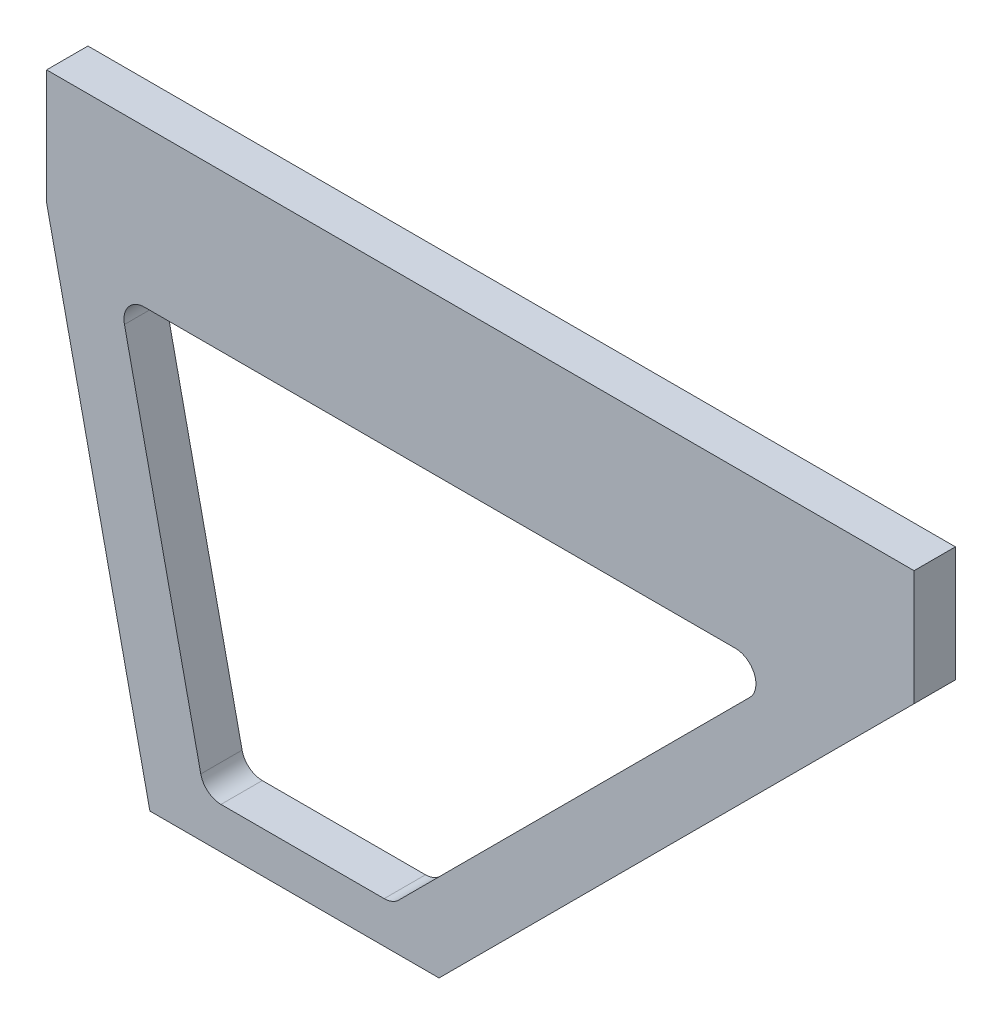
SolidWorks part; units mm, degrees
material "Zoltek Panex 33"
ref_plane "Plan de face" through (0, 0, 0) normal (0, 0, 1) x (1, 0, 0)
ref_plane "Plan de dessus" through (0, 0, 0) normal (0, 1, 0) x (1, 0, 0)
ref_plane "Plan de droite" through (0, 0, 0) normal (1, 0, 0) x (0, 0, -1)
sketch "Esquisse2" plane through (0, 0, 0) normal (0, 0, 1) x (1, 0, 0)
  line L0 (-30.1972, -50.239) -> (-5.1972, -165.239)
  line L1 (-30.1972, -50.239) -> (-30.1972, -22.339)
  line L2 (-30.1972, -22.339) -> (179.8028, -22.339)
  line L3 (179.8028, -22.339) -> (179.8028, -50.239)
  line L4 (179.8028, -50.239) -> (64.8028, -165.239)
  line L5 (64.8028, -165.239) -> (-5.1972, -165.239)
  line L6 (119.8028, -50.239) -> (869.8028, -50.239) construction
  line L7 (-30.1972, -22.339) -> (0, -22.339) construction
  line L8 (53.5896, -155.239) -> (148.5896, -60.239)
  line L9 (148.5896, -60.239) -> (-12.6729, -60.239)
  line L10 (-12.6729, -60.239) -> (7.9792, -155.239)
  line L11 (53.5896, -155.239) -> (7.9792, -155.239)
  point P11 (30.7844, -155.239)
  dimension "D1" = 210
  dimension "D2" = 70
  dimension "D3" = 45
  dimension "D4" = 115
  dimension "D5" = 15
  dimension "D6" = 10
  dimension "D7" = 15
  dimension "D8" = 10
extrude "Boss.-Extru.1" add sketch "Esquisse2" along normal mid plane 10
fillet "Fillet1" radius 5 4 edges at (148.5896, -60.239, 0) (-12.6729, -60.239, 0) (7.9792, -155.239, 0) (53.5896, -155.239, 0)
